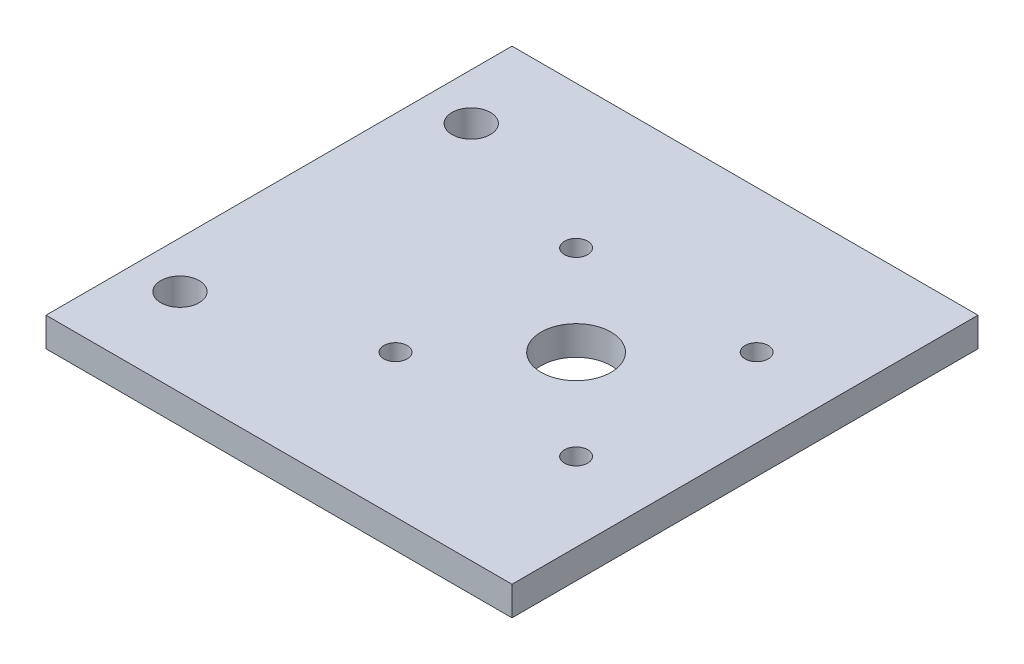
SolidWorks part; units mm, degrees
material "Lega 1060"
ref_plane "Piano frontale" through (0, 0, 0) normal (0, 0, 1) x (1, 0, 0)
ref_plane "Piano superiore" through (0, 0, 0) normal (0, 1, 0) x (1, 0, 0)
ref_plane "Piano destro" through (0, 0, 0) normal (1, 0, 0) x (0, 0, -1)
sketch "Schizzo1" plane through (0, 0, 0) normal (0, 0, 1) x (1, 0, 0)
  line L1 (0, 0) -> (80, 0)
  line L2 (0, 0) -> (0, 5)
  line L3 (0, 5) -> (80, 5)
  line L4 (80, 0) -> (80, 5)
  dimension "D1" = 5
  dimension "D2" = 80
extrude "Estrusione-Estrusione1" add sketch "Schizzo1" along normal blind 80
hole_wizard "Foro per Vite M6-1" positions "Schizzo3" profile "Schizzo2" hole size "M6" standard "ISO" end condition through all
sketch "Schizzo3" plane through (0, 5, 0) normal (0, 1, 0) x (1, 0, 0)
  line L0 (-9.8996, -40) -> (95.021, -40) construction
  line L2 (80, -80) -> (0, -80) construction
  line L3 (80, 0) -> (0, 0) construction
  line L4 (0, -80) -> (0, 0) construction
  point P0 (8, -15)
  point P1 (8, -65)
  dimension "D1" = 15
  dimension "D2" = 8
sketch "Schizzo2" plane through (8, 5, 15) normal (1, 0, 0) x (0, 0, 1)
  line L0 (0, 0) -> (0, 5)
  line L1 (0, 5) -> (3.3, 5)
  line L2 (3.3, 5) -> (3.3, 0)
  line L5 (3.3, 0) -> (0, 0)
  line L11 (0, -6.35) -> (0, 107.95) construction
  dimension "Thru Hole Dia." = 6.6
  dimension "Thru Hole Depth" = 5
sketch "Schizzo4" plane through (0, 5, 0) normal (0, 1, 0) x (1, 0, 0)
  line L0 (0, -80) -> (0, 0) construction
  line L3 (19.8289, -40) -> (54.8798, -40) construction
  line L4 (80, -80) -> (0, -80) construction
  line L5 (80, 0) -> (0, 0) construction
  circle A0 centre (51, -40) radius 6
  circle A1 centre (8, -15) radius 3.3 construction
  dimension "D1" = 12
  dimension "D2" = 43
extrude "Taglio-Estrusione1" cut sketch "Schizzo4" against normal through all
sketch "Schizzo6" plane through (0, 5, 0) normal (0, 1, 0) x (1, 0, 0)
  line L0 (42.0101, -40) -> (55.783, -40) construction
  line L1 (51, -40) -> (51, -30.1482) construction
  line L2 (80, -80) -> (0, -80) construction
  line L3 (80, 0) -> (0, 0) construction
  circle A0 centre (35.5, -24.5) radius 2
  circle A1 centre (66.5, -24.5) radius 2
  circle A2 centre (66.5, -55.5) radius 2
  circle A3 centre (35.5, -55.5) radius 2
  dimension "D1" = 4
  dimension "D2" = 31
  dimension "D3" = 31
  dimension "D4" = 15.5
extrude "Taglio-Estrusione3" cut sketch "Schizzo6" against normal through all
